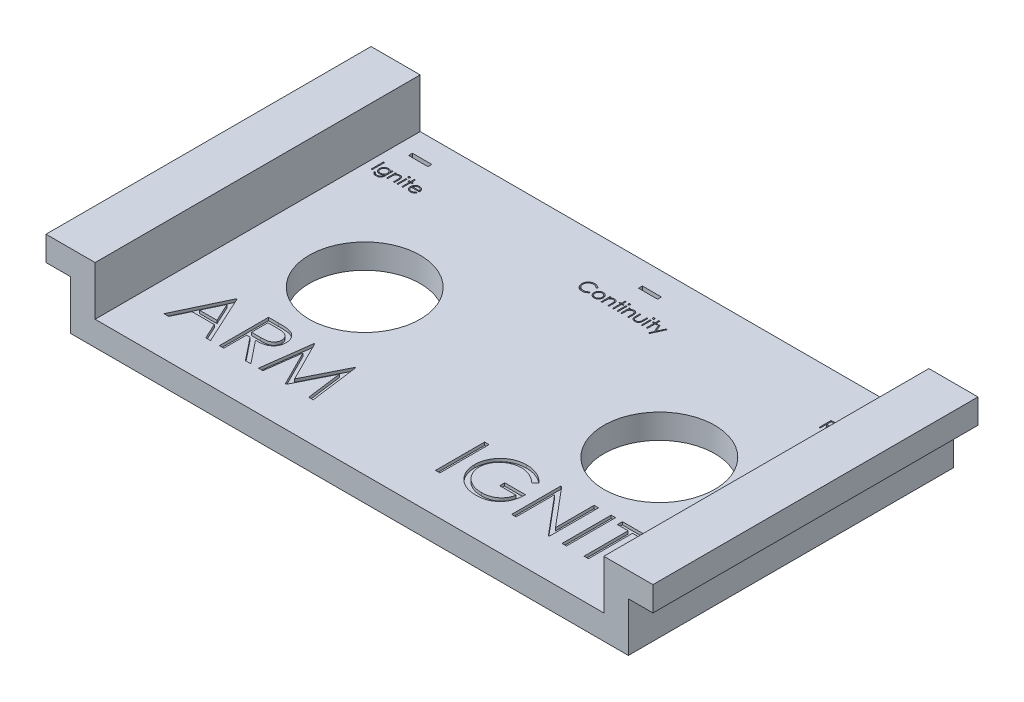
SolidWorks part; units mm, degrees
ref_plane "Front Plane" through (0, 0, 0) normal (0, 0, 1) x (1, 0, 0)
ref_plane "Top Plane" through (0, 0, 0) normal (0, 1, 0) x (1, 0, 0)
ref_plane "Right Plane" through (0, 0, 0) normal (1, 0, 0) x (0, 0, -1)
sketch "Çizim1" plane through (0, 0, 0) normal (0, 1, 0) x (1, 0, 0)
  line L1 (-72.136, -42.037) -> (72.136, -42.037)
  line L2 (-72.136, -42.037) -> (-72.136, 42.037)
  line L3 (-72.136, 42.037) -> (72.136, 42.037)
  line L4 (72.136, -42.037) -> (72.136, 42.037)
  line L5 (-72.136, -42.037) -> (72.136, 42.037) construction
  line L6 (-72.136, 42.037) -> (72.136, -42.037) construction
  point P0 (0, 0)
  dimension "D1" = 144.272
  dimension "D2" = 84.074
extrude "Yükseklik-Ekstrüzyon1" add sketch "Çizim1" along normal blind 6.35
sketch "Çizim2" plane through (-72.136, 0, 0) normal (-1, 0, 0) x (0, 0, 1)
  line L1 (-42.037, 6.35) -> (42.037, 6.35)
  line L2 (-42.037, 6.35) -> (-42.037, 19.05)
  line L3 (-42.037, 19.05) -> (42.037, 19.05)
  line L4 (42.037, 6.35) -> (42.037, 19.05)
  dimension "D1" = 84.074
  dimension "D2" = 12.7
extrude "Yükseklik-Ekstrüzyon2" add sketch "Çizim2" against normal blind 6.35
sketch "Çizim3" plane through (72.136, 0, 0) normal (1, 0, 0) x (0, 0, -1)
  line L1 (-42.037, 6.35) -> (42.037, 6.35)
  line L2 (-42.037, 6.35) -> (-42.037, 19.05)
  line L3 (-42.037, 19.05) -> (42.037, 19.05)
  line L4 (42.037, 6.35) -> (42.037, 19.05)
extrude "Yükseklik-Ekstrüzyon3" add sketch "Çizim3" against normal blind 6.35
sketch "Çizim4" plane through (72.136, 0, 0) normal (1, 0, 0) x (0, 0, -1)
  line L0 (42.037, 19.05) -> (42.037, 0) construction
  line L1 (-42.037, 19.05) -> (42.037, 19.05)
  line L2 (-42.037, 19.05) -> (-42.037, 12.7)
  line L3 (-42.037, 12.7) -> (42.037, 12.7)
  line L4 (42.037, 19.05) -> (42.037, 12.7)
  dimension "D1" = 6.35
sketch "Çizim6" plane through (-72.136, 0, 0) normal (-1, 0, 0) x (0, 0, 1)
  line L1 (-42.037, 19.05) -> (42.037, 19.05)
  line L2 (-42.037, 19.05) -> (-42.037, 12.7)
  line L3 (-42.037, 12.7) -> (42.037, 12.7)
  line L4 (42.037, 19.05) -> (42.037, 12.7)
extrude "Yükseklik-Ekstrüzyon4" add sketch "Çizim6" along normal blind 6.35
extrude "Yükseklik-Ekstrüzyon5" add sketch "Çizim4" along normal blind 6.35
sketch "Çizim7" plane through (0, 6.35, 0) normal (0, 1, 0) x (1, 0, 0)
  circle A0 centre (-38.1, 0) radius 14.351
  dimension "D1" = 28.702
  dimension "D2" = 38.1
extrude "Kes-Ekstrüzyon1" cut sketch "Çizim7" against normal blind 6.35
sketch "Çizim8" plane through (0, 6.35, 0) normal (0, 1, 0) x (1, 0, 0)
  circle A0 centre (38.1, 0) radius 14.351
  dimension "D1" = 28.702
  dimension "D2" = 38.1
extrude "Kes-Ekstrüzyon2" cut sketch "Çizim8" against normal blind 6.35
sketch "Çizim9" plane through (0, 6.35, 0) normal (0, 1, 0) x (1, 0, 0)
  line L0 (65.786, 42.037) -> (-65.786, 42.037) construction
  line L2 (65.786, 42.037) -> (65.786, -42.037) construction
  line L3 (57.436, 36.187) -> (61.436, 36.187)
  line L4 (57.436, 36.187) -> (57.436, 35.187)
  line L5 (57.436, 35.187) -> (61.436, 35.187)
  line L6 (61.436, 36.187) -> (61.436, 35.187)
  line L7 (57.436, 36.187) -> (61.436, 35.187) construction
  line L8 (57.436, 35.187) -> (61.436, 36.187) construction
  point P0 (59.436, 35.687)
  dimension "D1" = 6.35
  dimension "D2" = 6.35
  dimension "D4" = 4
  dimension "D5" = 1
extrude "Kes-Ekstrüzyon3" cut sketch "Çizim9" against normal blind 6.35
sketch "Çizim10" plane through (0, 6.35, 0) normal (0, 1, 0) x (1, 0, 0)
  line L1 (65.786, 42.037) -> (-65.786, 42.037) construction
  line L2 (-2.4613, 36.187) -> (2.4613, 36.187)
  line L3 (-2.4613, 36.187) -> (-2.4613, 35.187)
  line L4 (-2.4613, 35.187) -> (2.4613, 35.187)
  line L5 (2.4613, 36.187) -> (2.4613, 35.187)
  line L6 (-2.4613, 36.187) -> (2.4613, 35.187) construction
  line L7 (-2.4613, 35.187) -> (2.4613, 36.187) construction
  point P0 (0, 35.687)
  dimension "D1" = 1
  dimension "D2" = 6.35
  dimension "D3" = 4.9225
extrude "Kes-Ekstrüzyon4" cut sketch "Çizim10" against normal blind 6.35
sketch "Çizim11" plane through (0, 6.35, 0) normal (0, 1, 0) x (1, 0, 0)
  line L0 (65.786, 42.037) -> (-65.786, 42.037) construction
  text T0 "Continuity"
  dimension "D1" = 14.732
extrude "Kes-Ekstrüzyon5" cut sketch "Çizim11" against normal blind 0.762
sketch "Çizim12" plane through (0, 6.35, 0) normal (0, 1, 0) x (1, 0, 0)
  line L0 (65.786, 42.037) -> (-65.786, 42.037) construction
  text T0 "Radio"
  point P1 (50.3767, 27.305)
  point P2 (0, 0)
  point P5 (51.193, 27.305)
  point P6 (51.6595, 27.305)
  dimension "D1" = 14.732
extrude "Kes-Ekstrüzyon6" cut sketch "Çizim12" against normal blind 0.762
sketch "Çizim13" plane through (0, 6.35, 0) normal (0, 1, 0) x (1, 0, 0)
  line L0 (-65.786, -42.037) -> (65.786, -42.037) construction
  text T0 "ARM" font "Century Gothic" height 12.7
  dimension "D1" = 10.16
sketch "Çizim14" plane through (0, 6.35, 0) normal (0, 1, 0) x (1, 0, 0)
  line L0 (-65.786, -42.037) -> (65.786, -42.037) construction
  text T0 "IGNITE" font "Century Gothic" height 12.7
  dimension "D1" = 10.16
extrude "Kes-Ekstrüzyon7" cut sketch "Çizim13" against normal blind 0.762
extrude "Kes-Ekstrüzyon8" cut sketch "Çizim14" against normal blind 0.762
sketch "Çizim15" plane through (0, 6.35, 0) normal (0, 1, 0) x (1, 0, 0)
  line L0 (-65.786, -42.037) -> (-65.786, 42.037) construction
  line L2 (65.786, 42.037) -> (-65.786, 42.037) construction
  line L3 (-61.936, 36.187) -> (-56.936, 36.187)
  line L4 (-61.936, 36.187) -> (-61.936, 35.187)
  line L5 (-61.936, 35.187) -> (-56.936, 35.187)
  line L6 (-56.936, 36.187) -> (-56.936, 35.187)
  line L7 (-61.936, 36.187) -> (-56.936, 35.187) construction
  line L8 (-61.936, 35.187) -> (-56.936, 36.187) construction
  point P0 (-59.436, 35.687)
  dimension "D1" = 6.35
  dimension "D2" = 6.35
  dimension "D4" = 1
  dimension "D5" = 5
extrude "Kes-Ekstrüzyon9" cut sketch "Çizim15" against normal blind 6.35
sketch "Çizim16" plane through (0, 6.35, 0) normal (0, 1, 0) x (1, 0, 0)
  line L0 (65.786, 42.037) -> (-65.786, 42.037) construction
  text T0 "Ignite"
  point P1 (-64.7201, 27.305)
  point P4 (-64.1371, 27.305)
  dimension "D1" = 14.732
extrude "Kes-Ekstrüzyon10" cut sketch "Çizim16" against normal blind 0.762
